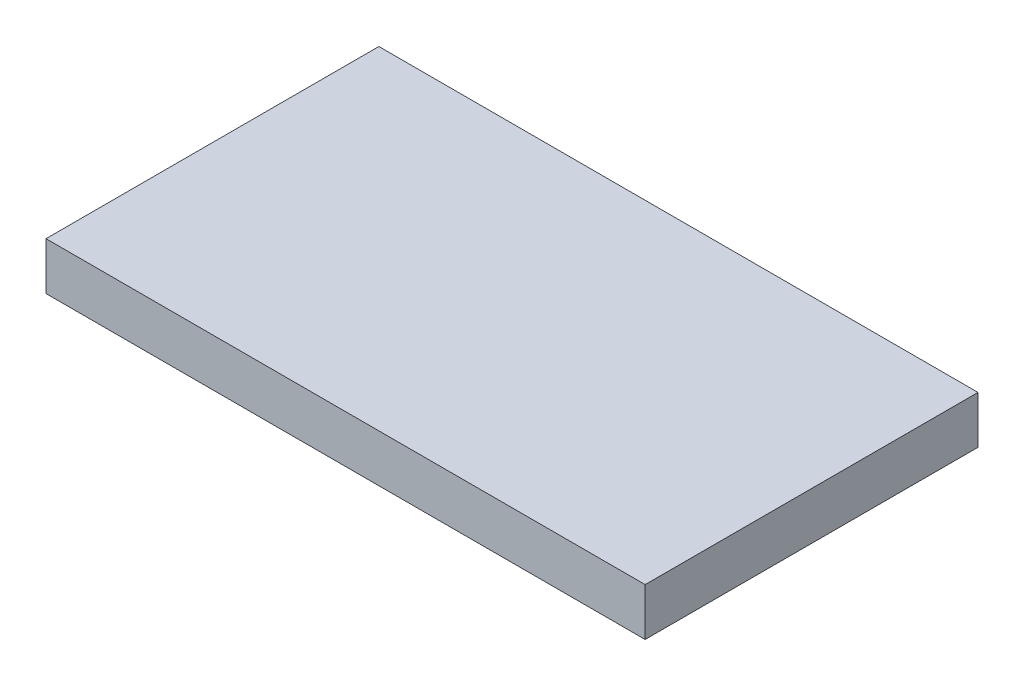
SolidWorks part; units mm, degrees
ref_plane "Front" through (0, 0, 0) normal (0, 0, 1) x (1, 0, 0)
ref_plane "Top" through (0, 0, 0) normal (0, 1, 0) x (1, 0, 0)
ref_plane "Right" through (0, 0, 0) normal (1, 0, 0) x (0, 0, -1)
sketch "Sketch1" plane through (0, 0, 0) normal (0, 1, 0) x (1, 0, 0)
  line L1 (-51.651, 20.3195) -> (11.349, 20.3195)
  line L2 (-51.651, 20.3195) -> (-51.651, -14.6805)
  line L3 (-51.651, -14.6805) -> (11.349, -14.6805)
  line L4 (11.349, 20.3195) -> (11.349, -14.6805)
  dimension "D1" = 63
  dimension "D2" = 35
extrude "Boss-Extrude1" add sketch "Sketch1" along normal blind 5
